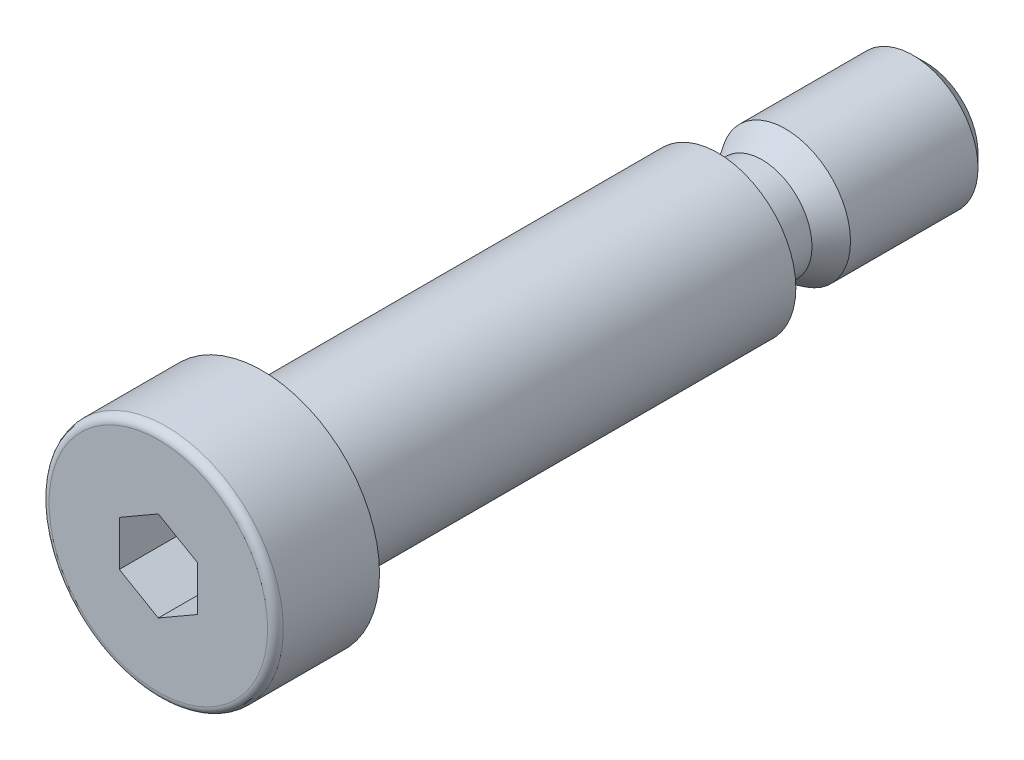
SolidWorks part; units mm, degrees
material "1.0545 (S355N)"
ref_plane "Płaszczyzna przednia" through (0, 0, 0) normal (0, 0, 1) x (1, 0, 0)
ref_plane "Płaszczyzna górna" through (0, 0, 0) normal (0, 1, 0) x (1, 0, 0)
ref_plane "Płaszczyzna prawa" through (0, 0, 0) normal (1, 0, 0) x (0, 0, -1)
sketch "Szkic1" plane through (0, 0, 0) normal (0, 1, 0) x (1, 0, 0)
  line L0 (5, 22.7) -> (3.85, 20.89)
  line L1 (9, -25.5) -> (-9, -25.5)
  line L2 (9, -25.5) -> (9, -17.5)
  line L3 (9, -17.5) -> (-9, -17.5)
  line L4 (-9, -25.5) -> (-9, -17.5)
  line L5 (6, -17.5) -> (-6, -17.5)
  line L6 (6, -17.5) -> (6, 17.5)
  line L7 (6, 17.5) -> (-6, 17.5)
  line L8 (-6, -17.5) -> (-6, 17.5)
  line L9 (-3.85, 17.5) -> (3.85, 17.5)
  line L10 (-3.85, 17.5) -> (-3.85, 20.89)
  line L11 (-3.85, 20.89) -> (3.85, 20.89)
  line L12 (3.85, 17.5) -> (3.85, 20.89)
  line L13 (5, 22.7) -> (5, 32.5)
  line L14 (5, 32.5) -> (4, 33.5)
  line L15 (4, 33.5) -> (-4, 33.5)
  line L16 (-4, 33.5) -> (-5, 32.5)
  line L17 (-5, 32.5) -> (-5, 22.7)
  line L18 (-5, 22.7) -> (-3.85, 20.89)
  line L19 (5, 22.7) -> (-5, 22.7) construction
  line L20 (5, 32.5) -> (-5, 32.5) construction
  line L21 (0, -19.9356) -> (0, 25.6583) construction
  line L22 (0, -25.5) -> (0, 33.5)
  point P4 (0, -17.5)
  point P14 (0, -17.5)
  point P15 (0, 17.5)
  point P16 (0, 17.5)
  point P17 (-6, 0)
  point P23 (0, 22.7)
  point P25 (0, 33.5)
  point P26 (0, 20.89)
  point P27 (0, 32.5)
  dimension "D1" = 18
  dimension "D2" = 8
  dimension "D3" = 12
  dimension "l1" = 35
  dimension "D5" = 7.7
  dimension "D6" = 16
  dimension "D7" = 10
  dimension "D8" = 8
  dimension "D9" = 1
  dimension "D10" = 1.81
  dimension "D11" = 9.8
revolve "Obrót1" add sketch "Szkic1" angle 360 about L22
sketch "Szkic2" plane through (0, 0, 25.5) normal (0, 0, 1) x (1, 0, 0)
  line L1 (3, 1.7321) -> (0, 3.4641)
  line L2 (0, 3.4641) -> (-3, 1.7321)
  line L3 (-3, 1.7321) -> (-3, -1.7321)
  line L4 (-3, -1.7321) -> (0, -3.4641)
  line L5 (0, -3.4641) -> (3, -1.7321)
  line L6 (3, -1.7321) -> (3, 1.7321)
  circle A0 centre (0, 0) radius 3 construction
  dimension "D1" = 6
extrude "Wytnij-wyciągnięcie1" cut sketch "Szkic2" against normal blind 4.9
fillet "Zaokrąglenie1" radius 0.6 1 edges at (9, 0, 25.5)
